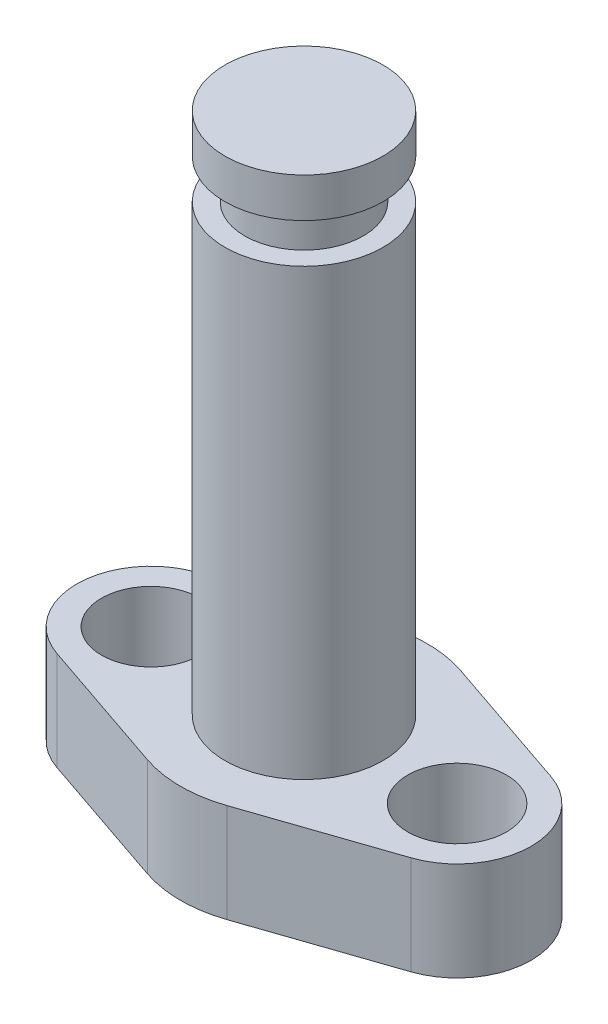
SolidWorks part; units mm, degrees
ref_plane "Front Plane" through (0, 0, 0) normal (0, 0, 1) x (1, 0, 0)
ref_plane "Top Plane" through (0, 0, 0) normal (0, 1, 0) x (1, 0, 0)
ref_plane "Right Plane" through (0, 0, 0) normal (1, 0, 0) x (0, 0, -1)
sketch "Sketch1" plane through (0, 0, 0) normal (0, 1, 0) x (1, 0, 0)
  line L0 (-8.9597, 3.5495) -> (-2.0161, 5.9159)
  line L1 (-8.9597, -3.5495) -> (-2.0161, -5.9159)
  line L2 (2.0161, 5.9159) -> (8.9597, 3.5495)
  line L3 (8.9597, -3.5495) -> (2.0161, -5.9159)
  circle A0 centre (0, 0) radius 4 construction
  circle A1 centre (0, 0) radius 6.25
  circle A2 centre (7.75, 0) radius 2.5
  circle A3 centre (-7.75, 0) radius 2.5
  circle A4 centre (-7.75, 0) radius 3.75
  circle A5 centre (7.75, 0) radius 3.75
  point P18 (18, 0)
  dimension "D1" = 7.5
  dimension "D2" = 8
  dimension "D3" = 12.5
  dimension "D4" = 5
extrude "Boss-Extrude1" add sketch "Sketch1" along normal blind 5 contours A1 A4 A3 | A1 A4 A3 | A5 A1 A4 | A4 L1 A1 | A5 A1 L3 | A1 A5 A2 | A5 A1 A2 | A5 L2 A1 | A4 A1 L0
sketch "Sketch2" plane through (0, 5, 0) normal (0, 1, 0) x (1, 0, 0)
  line L0 (0, -6.25) -> (0, 6.25) construction
  line L1 (11.5, 0) -> (-11.5, 0) construction
  arc A0 (-2.0161, -5.9159) -> (2.0161, -5.9159) centre (0, 0) ccw construction
  arc A1 (2.0161, 5.9159) -> (-2.0161, 5.9159) centre (0, 0) ccw construction
  arc A2 (8.9597, -3.5495) -> (8.9597, 3.5495) centre (7.75, 0) ccw construction
  arc A3 (-8.9597, 3.5495) -> (-8.9597, -3.5495) centre (-7.75, 0) ccw construction
  circle A4 centre (0, 0) radius 4
extrude "Boss-Extrude2" add sketch "Sketch2" along normal blind 22.5
sketch "Sketch3" plane through (0, 27.5, 0) normal (0, 1, 0) x (1, 0, 0)
  circle A0 centre (0, 0) radius 3
  dimension "D1" = 6
extrude "Boss-Extrude3" add sketch "Sketch3" along normal blind 2
sketch "Sketch4" plane through (0, 29.5, 0) normal (0, 1, 0) x (1, 0, 0)
  circle A0 centre (0, 0) radius 4
extrude "Boss-Extrude4" add sketch "Sketch4" along normal blind 2
